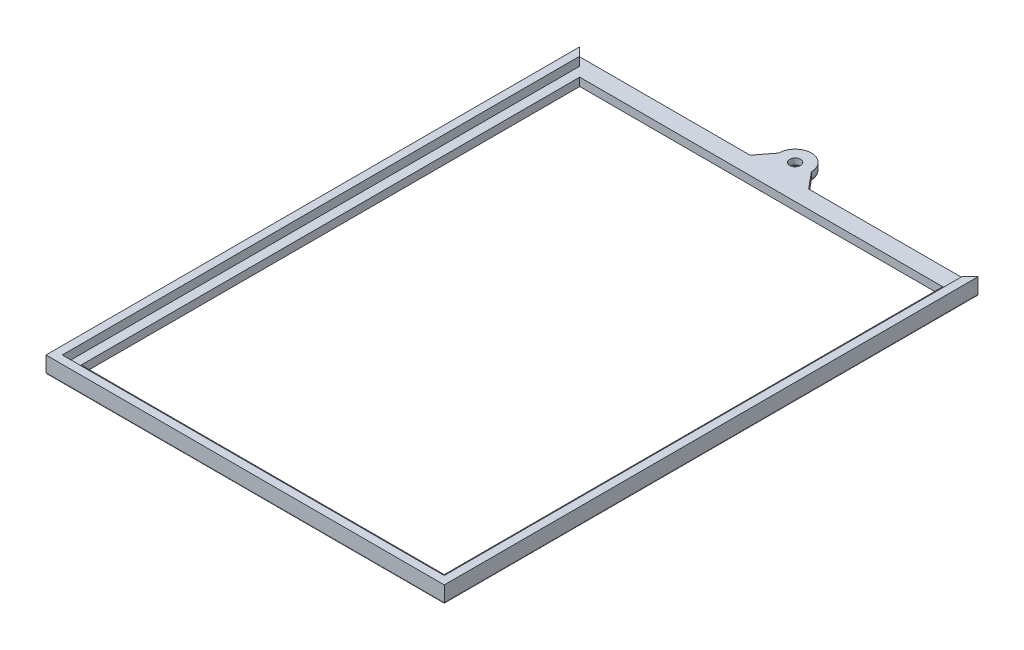
SolidWorks part; units mm, degrees
ref_plane "Спереди" through (0, 0, 0) normal (0, 0, 1) x (1, 0, 0)
ref_plane "Сверху" through (0, 0, 0) normal (0, 1, 0) x (1, 0, 0)
ref_plane "Справа" through (0, 0, 0) normal (1, 0, 0) x (0, 0, -1)
sketch "Эскиз1" plane through (0, 0, 0) normal (0, 1, 0) x (1, 0, 0)
  line L0 (36.75, 49.25) -> (5.5, 49.25)
  line L1 (35, -47.5) -> (-35, -47.5) construction
  line L2 (35, -47.5) -> (35, 47.5) construction
  line L3 (35, 47.5) -> (-35, 47.5) construction
  line L4 (-35, -47.5) -> (-35, 47.5) construction
  line L5 (35, -47.5) -> (-35, 47.5) construction
  line L6 (35, 47.5) -> (-35, -47.5) construction
  line L7 (-36.75, -49.25) -> (-36.75, 49.25)
  line L8 (36.75, -49.25) -> (-36.75, -49.25)
  line L9 (36.75, -49.25) -> (36.75, 49.25)
  line L10 (33.5, -46) -> (-33.5, -46)
  line L11 (-33.5, -46) -> (-33.5, 46)
  line L12 (33.5, 46) -> (-33.5, 46)
  line L13 (33.5, -46) -> (33.5, 46)
  line L14 (-5.3005, 49.25) -> (-3, 52.25)
  line L15 (3, 52.25) -> (5.5, 49.25)
  line L16 (-5.3005, 49.25) -> (-36.75, 49.25)
  line L18 (36.75, 49.25) -> (-36.75, 49.25) construction
  circle A0 centre (0, 52.25) radius 1
  arc A1 (3, 52.25) -> (-3, 52.25) centre (0, 52.25) ccw
  point P0 (0, 0)
  point P14 (0, 49.25)
  point P15 (0, 52.25)
  point P19 (0, 49.25)
  point P20 (-3, 52.25)
  point P21 (3, 52.25)
  point P22 (-2.8005, 49.25)
  point P23 (-5.3005, 49.25)
  point P26 (3, 49.25)
  point P27 (5.5, 49.25)
  dimension "D5" = 2
  dimension "D6" = 6
  dimension "D1" = 70
  dimension "D2" = 95
  dimension "D7" = 0
  dimension "D8" = 2.5
  dimension "D9" = 2.5
  dimension "D3" = 1.75
  dimension "D4" = 1.5
extrude "Бобышка-Вытянуть1" add sketch "Эскиз1" along normal blind 1.5
sketch "Эскиз2" plane through (0, 1.5, 0) normal (0, 1, 0) x (1, 0, 0)
  line L0 (-3, 52.25) -> (-5.3005, 49.25) construction
  line L1 (36.75, -49.25) -> (-36.75, -49.25)
  line L2 (36.75, -49.25) -> (36.75, 49.25)
  line L3 (36.75, 49.25) -> (5.5, 49.25) construction
  line L4 (-36.75, -49.25) -> (-36.75, 49.25)
  line L5 (36.75, -49.25) -> (-36.75, 49.25) construction
  line L6 (36.75, 49.25) -> (-36.75, -49.25) construction
  line L7 (35.25, -47.75) -> (-35.25, -47.75)
  line L8 (35.25, -47.75) -> (35.25, 47.75)
  line L9 (35.25, 47.75) -> (-35.25, 47.75) construction
  line L10 (-35.25, -47.75) -> (-35.25, 47.75)
  line L11 (35.25, -47.75) -> (-35.25, 47.75) construction
  line L12 (35.25, 47.75) -> (-35.25, -47.75) construction
  line L13 (-35.25, 47.75) -> (-36.75, 49.25)
  line L14 (5.5, 49.25) -> (3, 52.25) construction
  line L15 (-5.3005, 49.25) -> (-36.75, 49.25)
  line L16 (35.25, 47.75) -> (36.75, 49.25)
  circle A0 centre (0, 52.25) radius 1 construction
  arc A1 (3, 52.25) -> (-3, 52.25) centre (0, 52.25) ccw construction
  point P0 (0, 0)
  point P7 (0, 0)
  line M9 (36.75, -49.25) -> (36.75, 49.25)
  line M15 (-36.75, 49.25) -> (-36.75, -49.25)
  line M16 (-36.75, -49.25) -> (36.75, -49.25)
  dimension "D1" = 1.5
  dimension "D2" = 1.5
extrude "Бобышка-Вытянуть2" add sketch "Эскиз2" along normal blind 1.6 contours L16 L8 L7 L10 L13 M15 M16 M9
fillet "Скругление1" radius 0.3 8 edges at (-21.0253, 0, -49.25) (-4.1503, 0, -50.75) (0, 0, -55.25) (4.25, 0, -50.75) (21.125, 0, -49.25) (36.75, 0, 0) (0, 0, 49.25) (-36.75, 0, 0)
fillet "Скругление2" radius 0.5 1 edges at (0, 0, -51.25)
